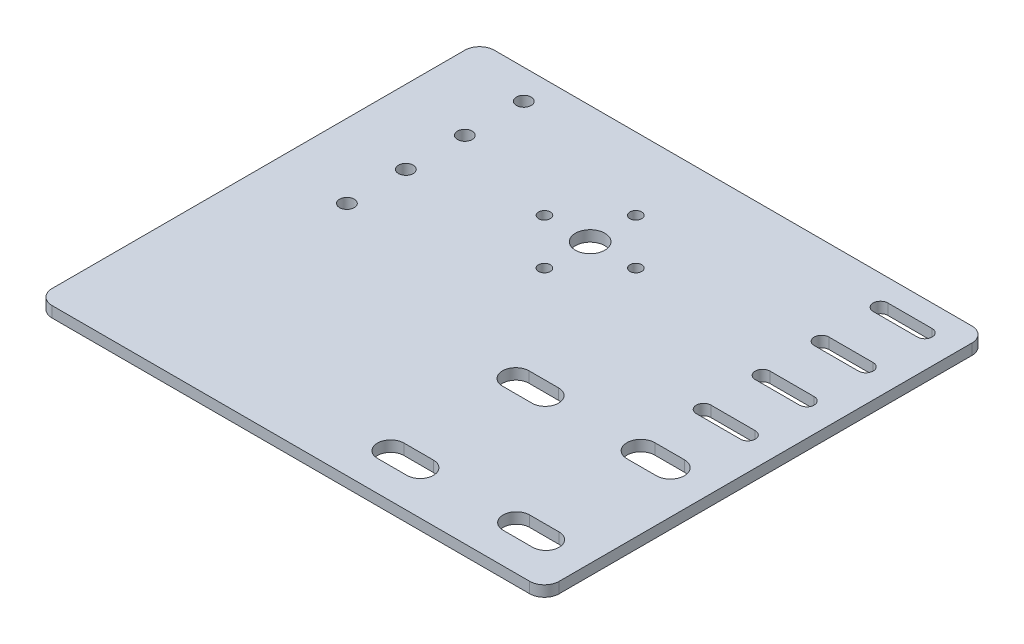
SolidWorks part; units mm, degrees
material "6061 合金"
ref_plane "前视基准面" through (0, 0, 0) normal (0, 0, 1) x (1, 0, 0)
ref_plane "上视基准面" through (0, 0, 0) normal (0, 1, 0) x (1, 0, 0)
ref_plane "右视基准面" through (0, 0, 0) normal (1, 0, 0) x (0, 0, -1)
sketch "草图2" plane through (0, 0, 0) normal (0, 0, 1) x (1, 0, 0)
  line L0 (0, 48.4298) -> (0, -52.4927) construction
  line L1 (0, 0) -> (0, 3.6765)
  line L2 (0, 3.6765) -> (-62.5, 3.6765)
  line L3 (-62.5, 3.6765) -> (-62.5, 0)
  line L4 (-62.5, 0) -> (0, 0)
  dimension "D1" = 62.5
extrude "凸台-拉伸1" add sketch "草图2" along normal mid plane 80
mirror "镜向1" about plane through (0, 0, 40) normal (-1, 0, 0) of "凸台-拉伸1"
sketch "草图4" plane through (0, 3.6765, 0) normal (0, 1, 0) x (1, 0, 0)
  line L0 (-62.5, 40) -> (-52.5, 40) construction
  line L1 (62.5, 40) -> (-62.5, 40) construction
  line L2 (-52.5, 40) -> (-52.5, -40) construction
  line L3 (62.5, -40) -> (-62.5, -40) construction
  line L4 (-52.5, 0) -> (-52.5, 10) construction
  line L5 (-52.5, 10) -> (-52.5, 30) construction
  line L6 (-74.3544, 0) -> (73.0384, 0) construction
  circle A0 centre (0, 0) radius 15.5 construction
  circle A1 centre (0, 15.5) radius 2
  circle A2 centre (15.5, 0) radius 2
  circle A3 centre (0, -15.5) radius 2
  circle A4 centre (-15.5, 0) radius 2
  circle A5 centre (0, 0) radius 5
  circle A6 centre (-52.5, 10) radius 2.5
  circle A7 centre (-52.5, 30) radius 2.5
  circle A8 centre (-52.5, -10) radius 2.5
  circle A9 centre (-52.5, -30) radius 2.5
  point P14 (0, 0)
  dimension "D1" = 4
extrude "切除-拉伸1" cut sketch "草图4" against normal through all
sketch "草图5" plane through (0, 0, 40) normal (0, 0, 1) x (1, 0, 0)
  line L4 (-62.5, 0) -> (62.5, 0)
  line L5 (62.5, 0) -> (62.5, 3.6765)
  line L6 (62.5, 3.6765) -> (-62.5, 3.6765)
  line L7 (-62.5, 3.6765) -> (-62.5, 0)
  line L8 (-62.5, 0) -> (62.5, 0)
  line L10 (62.5, 3.6765) -> (-62.5, 3.6765)
  line L11 (-62.5, 3.6765) -> (-62.5, 0)
  line L14 (62.5, 0) -> (62.5, 3.6765)
  dimension "D1" = 0
extrude "凸台-拉伸3" add sketch "草图5" along normal blind 50
sketch "草图6" plane through (62.5, 0, 0) normal (1, 0, 0) x (0, 0, -1)
  line L4 (40, 0) -> (40, 3.6765)
  line L5 (40, 3.6765) -> (-90, 3.6765)
  line L6 (-90, 3.6765) -> (-90, 0)
  line L7 (-90, 0) -> (40, 0)
  line L8 (40, 0) -> (40, 3.6765)
  line L9 (40, 3.6765) -> (-90, 3.6765)
  line L10 (-90, 3.6765) -> (-90, 0)
  line L11 (-90, 0) -> (40, 0)
  dimension "D1" = 0
extrude "凸台-拉伸4" add sketch "草图6" along normal blind 12
sketch "草图7" plane through (0, 3.6765, 0) normal (0, 1, 0) x (1, 0, 0)
  line L0 (74.5, 40) -> (68.5, 40) construction
  line L1 (74.5, 40) -> (-62.5, 40) construction
  line L2 (68.5, 40) -> (68.5, -90) construction
  line L3 (74.5, -90) -> (-62.5, -90) construction
  line L4 (-52.5, 30) -> (68.5, 30) construction
  line L5 (-52.5, 10) -> (68.5, 10) construction
  line L6 (-52.5, -10) -> (68.5, -10) construction
  line L7 (-52.5, -30) -> (68.5, -30) construction
  circle A0 centre (68.5, 30) radius 2.5
  circle A1 centre (68.5, 10) radius 2.5
  circle A2 centre (68.5, -10) radius 2.5
  circle A3 centre (68.5, -30) radius 2.5
extrude "切除-拉伸2" cut sketch "草图7" against normal through all
sketch "草图8" plane through (74.5, 0, 0) normal (1, 0, 0) x (0, 0, -1)
  line L4 (-90, 0) -> (40, 0)
  line L5 (40, 0) -> (40, 3.6765)
  line L6 (40, 3.6765) -> (-90, 3.6765)
  line L7 (-90, 3.6765) -> (-90, 0)
  line L8 (-90, 0) -> (40, 0)
  line L9 (40, 0) -> (40, 3.6765)
  line L10 (40, 3.6765) -> (-90, 3.6765)
  line L11 (-90, 3.6765) -> (-90, 0)
  dimension "D1" = 0
extrude "凸台-拉伸5" add sketch "草图8" along normal blind 20
sketch "草图10" plane through (0, 3.6765, 0) normal (0, 1, 0) x (1, 0, 0)
  line L0 (68.5, 30) -> (83.5, 30) construction
  line L1 (68.5, 32.5) -> (83.5, 32.5)
  line L2 (68.5, 27.5) -> (83.5, 27.5)
  line L3 (68.5, 10) -> (83.5, 10) construction
  line L4 (68.5, 12.5) -> (83.5, 12.5)
  line L5 (68.5, 7.5) -> (83.5, 7.5)
  line L6 (68.5, -10) -> (83.5, -10) construction
  line L7 (68.5, -7.5) -> (83.5, -7.5)
  line L8 (68.5, -12.5) -> (83.5, -12.5)
  line L9 (68.5, -30) -> (83.5, -30) construction
  line L10 (68.5, -27.5) -> (83.5, -27.5)
  line L11 (68.5, -32.5) -> (83.5, -32.5)
  arc A0 (68.5, 32.5) -> (68.5, 27.5) centre (68.5, 30) ccw
  arc A1 (83.5, 27.5) -> (83.5, 32.5) centre (83.5, 30) ccw
  arc A2 (68.5, 12.5) -> (68.5, 7.5) centre (68.5, 10) ccw
  arc A3 (83.5, 7.5) -> (83.5, 12.5) centre (83.5, 10) ccw
  arc A4 (68.5, -7.5) -> (68.5, -12.5) centre (68.5, -10) ccw
  arc A5 (83.5, -12.5) -> (83.5, -7.5) centre (83.5, -10) ccw
  arc A6 (68.5, -27.5) -> (68.5, -32.5) centre (68.5, -30) ccw
  arc A7 (83.5, -32.5) -> (83.5, -27.5) centre (83.5, -30) ccw
  point P3 (76, 30)
  point P11 (76, 10)
  point P16 (76, -10)
  point P24 (76, -30)
extrude "切除-拉伸4" cut sketch "草图10" against normal through all
sketch "草图11" plane through (-62.5, 0, 0) normal (-1, 0, 0) x (0, 0, 1)
  line L4 (-40, 3.6765) -> (-40, 0)
  line L5 (-40, 0) -> (90, 0)
  line L6 (90, 0) -> (90, 3.6765)
  line L7 (90, 3.6765) -> (-40, 3.6765)
  line L8 (-40, 3.6765) -> (-40, 0)
  line L9 (-40, 0) -> (90, 0)
  line L10 (90, 0) -> (90, 3.6765)
  line L11 (90, 3.6765) -> (-40, 3.6765)
  dimension "D1" = 0
extrude "凸台-拉伸6" add sketch "草图11" along normal blind 15
sketch "草图12" plane through (0, 0, 90) normal (0, 0, 1) x (1, 0, 0)
  line L4 (94.5, 3.6765) -> (-77.5, 3.6765)
  line L5 (-77.5, 3.6765) -> (-77.5, 0)
  line L6 (-77.5, 0) -> (94.5, 0)
  line L7 (94.5, 0) -> (94.5, 3.6765)
  line L8 (94.5, 3.6765) -> (-77.5, 3.6765)
  line L10 (-77.5, 0) -> (94.5, 0)
  line L11 (94.5, 0) -> (94.5, 3.6765)
  line L13 (-77.5, 3.6765) -> (-77.5, 0)
  dimension "D1" = 0
extrude "凸台-拉伸7" add sketch "草图12" along normal blind 20
sketch "草图13" plane through (0, 3.6765, 0) normal (0, 1, 0) x (1, 0, 0)
  line L0 (94.5, -82.8095) -> (80, -82.8095) construction
  line L1 (94.5, 40) -> (94.5, -110) construction
  line L2 (80, -58.7868) -> (80, -52.7868) construction
  line L4 (94.5, -110) -> (-77.5, -110) construction
  line L5 (58.7868, -80) -> (80, -58.7868) construction
  line L6 (80, -58.7868) -> (70, -58.7868) construction
  line L7 (80, -63.2868) -> (70, -63.2868) construction
  line L8 (80, -54.2868) -> (70, -54.2868) construction
  line L9 (80, -101.0129) -> (70, -101.0129) construction
  line L10 (80, -105.5129) -> (70, -105.5129) construction
  line L11 (80, -96.5129) -> (70, -96.5129) construction
  line L12 (58.7868, -80) -> (37.5736, -58.7868) construction
  line L15 (58.7868, -80) -> (37.5736, -101.2132) construction
  line L16 (37.5736, -58.7868) -> (27.5736, -58.7868) construction
  line L17 (37.5736, -63.2868) -> (27.5736, -63.2868) construction
  line L18 (37.5736, -54.2868) -> (27.5736, -54.2868) construction
  line L19 (37.5736, -101.2132) -> (27.5736, -101.2132) construction
  line L20 (37.5736, -105.7132) -> (27.5736, -105.7132) construction
  line L21 (37.5736, -96.7132) -> (27.5736, -96.7132) construction
  line L22 (37.5736, -101.2132) -> (37.5736, -95.2132) construction
  line L23 (37.5736, -58.7868) -> (37.5736, -52.7868) construction
  line L24 (80, -52.7868) -> (70, -52.7868) construction
  line L25 (80, -101.0129) -> (80, -95.0129) construction
  line L26 (80, -95.0129) -> (70, -95.0129) construction
  line L27 (80, -99.5129) -> (70, -99.5129)
  line L28 (80, -90.5129) -> (70, -90.5129)
  line L29 (37.5736, -95.2132) -> (27.5736, -95.2132) construction
  line L30 (37.5736, -99.7132) -> (27.5736, -99.7132)
  line L31 (37.5736, -90.7132) -> (27.5736, -90.7132)
  line L32 (37.5736, -52.7868) -> (27.5736, -52.7868) construction
  line L33 (37.5736, -57.2868) -> (27.5736, -57.2868)
  line L34 (37.5736, -48.2868) -> (27.5736, -48.2868)
  line L35 (80, -57.5201) -> (70, -57.5201)
  line L38 (80, -48.0535) -> (70, -48.0535)
  circle A1 centre (58.7868, -80) radius 30 construction
  arc A6 (80, -63.2868) -> (80, -54.2868) centre (80, -58.7868) ccw construction
  arc A7 (70, -54.2868) -> (70, -63.2868) centre (70, -58.7868) ccw construction
  arc A8 (80, -105.5129) -> (80, -96.5129) centre (80, -101.0129) ccw construction
  arc A9 (70, -96.5129) -> (70, -105.5129) centre (70, -101.0129) ccw construction
  arc A12 (37.5736, -63.2868) -> (37.5736, -54.2868) centre (37.5736, -58.7868) ccw construction
  arc A13 (27.5736, -54.2868) -> (27.5736, -63.2868) centre (27.5736, -58.7868) ccw construction
  arc A14 (37.5736, -105.7132) -> (37.5736, -96.7132) centre (37.5736, -101.2132) ccw construction
  arc A15 (27.5736, -96.7132) -> (27.5736, -105.7132) centre (27.5736, -101.2132) ccw construction
  arc A16 (80, -99.5129) -> (80, -90.5129) centre (80, -95.0129) ccw
  arc A17 (70, -90.5129) -> (70, -99.5129) centre (70, -95.0129) ccw
  arc A18 (37.5736, -99.7132) -> (37.5736, -90.7132) centre (37.5736, -95.2132) ccw
  arc A19 (27.5736, -90.7132) -> (27.5736, -99.7132) centre (27.5736, -95.2132) ccw
  arc A20 (37.5736, -57.2868) -> (37.5736, -48.2868) centre (37.5736, -52.7868) ccw
  arc A21 (27.5736, -48.2868) -> (27.5736, -57.2868) centre (27.5736, -52.7868) ccw
  arc A24 (80, -57.5201) -> (80, -48.0535) centre (80, -52.7868) ccw
  arc A25 (70, -48.0535) -> (70, -57.5201) centre (70, -52.7868) ccw
  point P11 (75, -101.0129)
  point P13 (75, -58.7868)
  point P18 (32.5736, -58.7868)
  point P22 (58.7868, -80)
  point P35 (32.5736, -101.2132)
  point P46 (75, -52.7868)
  point P50 (75, -95.0129)
  point P55 (32.5736, -95.2132)
  point P61 (32.5736, -52.7868)
  dimension "D5" = 6
  dimension "D2" = 8.9871
extrude "切除-拉伸5" cut sketch "草图13" against normal through all
fillet "圆角2" radius 5 4 edges at (-77.5, 1.8382, -40) (94.5, 1.8382, -40) (94.5, 1.8382, 110) (-77.5, 1.8382, 110)
sketch "草图14" plane through (0, 3.6765, 0) normal (0, 1, 0) x (1, 0, 0)
  line L0 (-52.5, 30) -> (-52.5, -30) construction
  line L1 (-71.2818, 0) -> (-29.9608, 0) construction
  line L2 (-52.5, 0) -> (-42.5, 0) construction
  line L3 (-42.5, 0) -> (-42.5, 25) construction
  line L4 (-42.5, 25) -> (-62.5, 25) construction
  circle A0 centre (-42.5, 0) radius 2.5
  circle A1 centre (-42.5, 25) radius 2.5
  circle A2 centre (-62.5, 25) radius 2.5
  circle A3 centre (-62.5, 0) radius 2.5
  circle A4 centre (-42.5, -25) radius 2.5
  circle A5 centre (-62.5, -25) radius 2.5
